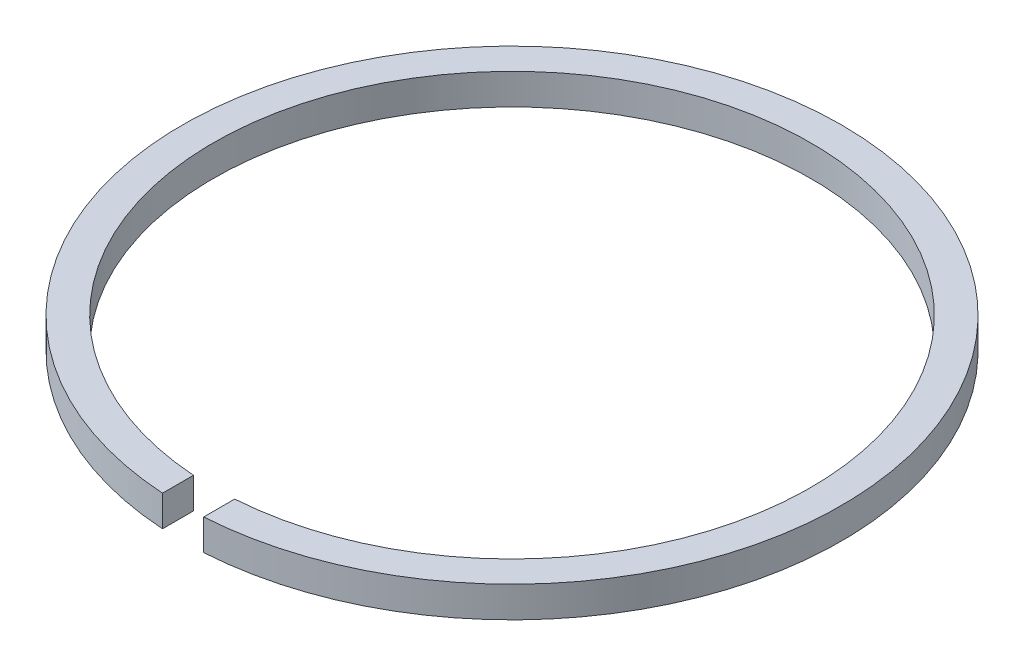
SolidWorks part; units mm, degrees
ref_plane "Front Plane" through (0, 0, 0) normal (0, 0, 1) x (1, 0, 0)
ref_plane "Top Plane" through (0, 0, 0) normal (0, 1, 0) x (1, 0, 0)
ref_plane "Right Plane" through (0, 0, 0) normal (1, 0, 0) x (0, 0, -1)
sketch "Sketch1" plane through (0, 0, 0) normal (0, 1, 0) x (1, 0, 0)
  line L0 (0, 0) -> (0, -18.9563) construction
  line L1 (-1, -14.4655) -> (-1, -15.9687)
  line L2 (1, -14.4655) -> (1, -15.9687)
  arc A0 (1, -14.4655) -> (-1, -14.4655) centre (0, 0) ccw
  arc A1 (1, -15.9687) -> (-1, -15.9687) centre (0, 0) ccw
  dimension "D1" = 29
  dimension "D2" = 32
  dimension "D3" = 2
  dimension "D4" = 1
extrude "Boss-Extrude1" add sketch "Sketch1" along normal blind 1.5
